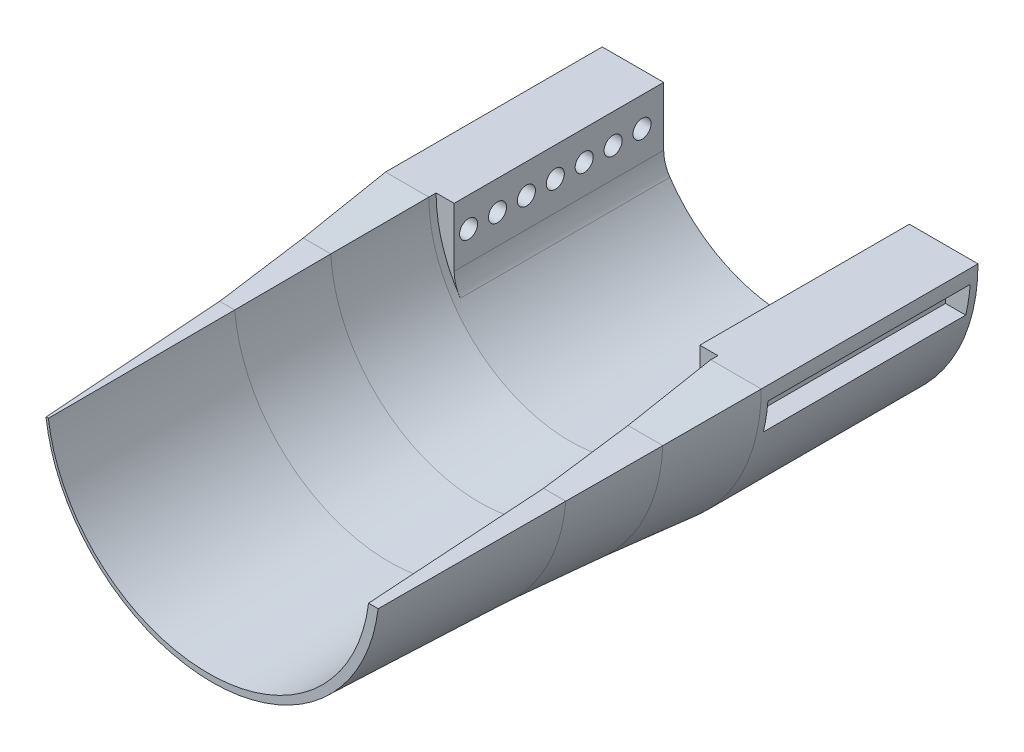
SolidWorks part; units mm, degrees
ref_plane "Front Plane" through (0, 0, 0) normal (0, 0, 1) x (1, 0, 0)
ref_plane "Top Plane" through (0, 0, 0) normal (0, 1, 0) x (1, 0, 0)
ref_plane "Right Plane" through (0, 0, 0) normal (1, 0, 0) x (0, 0, -1)
sketch "Sketch1" plane through (0, 0, 0) normal (0, 0, 1) x (1, 0, 0)
  line L0 (-39.8456, 0) -> (-40, 0) construction
  line L1 (-40, 10) -> (-40, -20) construction
  line L2 (-40, 0) -> (38, 0) construction
  line L3 (38, 20) -> (38, -20) construction
  line L4 (-39.8456, 0) -> (-52, 0)
  line L5 (38, 0) -> (52, 0)
  circle A0 centre (0, 0) radius 52 construction
  arc A1 (-40, 0) -> (38, 0) centre (-1, 0) ccw
  arc A2 (-52, 0) -> (52, 0) centre (0, 0) ccw
extrude "Boss-Extrude1" add sketch "Sketch1" along normal blind 60 contours L4 A2 L5 A1
sketch "Sketch2" plane through (0, 0, 60) normal (0, 0, 1) x (1, 0, 0)
  line L2 (-40, 0) -> (-52, 0)
  line L3 (52, 0) -> (38, 0)
  line L4 (-40, 0) -> (-52, 0)
  line L5 (52, 0) -> (38, 0)
  arc A2 (-52, 0) -> (52, 0) centre (0, 0) ccw
  arc A3 (-40, 0) -> (38, 0) centre (-1, 0) ccw
  arc A4 (-52, 0) -> (52, 0) centre (0, 0) ccw
  arc A5 (-40, 0) -> (38, 0) centre (-1, 0) ccw
  dimension "D1" = 0
extrude "Boss-Extrude2" add sketch "Sketch2" along normal blind 25 draft 5
sketch "Sketch3" plane through (0, 0, 85) normal (0, 0, 1) x (1, 0, 0)
  line L2 (-42.1291, -2.1872) -> (-49.7647, -2.1872)
  line L3 (49.7647, -2.1872) -> (40.1291, -2.1872)
  line L4 (-42.1291, -2.1872) -> (-49.7647, -2.1872)
  line L5 (49.7647, -2.1872) -> (40.1291, -2.1872)
  arc A2 (-42.1291, -2.1872) -> (40.1291, -2.1872) centre (-1, 0) ccw
  arc A3 (-49.7647, -2.1872) -> (49.7647, -2.1872) centre (0, 0) ccw
  arc A4 (-42.1291, -2.1872) -> (40.1291, -2.1872) centre (-1, 0) ccw
  arc A5 (-49.7647, -2.1872) -> (49.7647, -2.1872) centre (0, 0) ccw
  dimension "D1" = 0
extrude "Boss-Extrude3" add sketch "Sketch3" along normal blind 25 draft 4
sketch "Sketch4" plane through (0, 0, 110) normal (0, 0, 1) x (1, 0, 0)
  line L2 (-43.7547, -3.9354) -> (-47.9032, -3.9354)
  line L3 (47.9032, -3.9354) -> (41.7547, -3.9354)
  line L4 (-43.7547, -3.9354) -> (-47.9032, -3.9354)
  line L5 (47.9032, -3.9354) -> (41.7547, -3.9354)
  arc A2 (-43.7547, -3.9354) -> (41.7547, -3.9354) centre (-1, 0) ccw
  arc A3 (-47.9032, -3.9354) -> (47.9032, -3.9354) centre (0, 0) ccw
  arc A4 (-43.7547, -3.9354) -> (41.7547, -3.9354) centre (-1, 0) ccw
  arc A5 (-47.9032, -3.9354) -> (47.9032, -3.9354) centre (0, 0) ccw
  dimension "D1" = 0
extrude "Boss-Extrude4" add sketch "Sketch4" along normal blind 50 draft 2
sketch "Sketch5" plane through (0, 0, 0) normal (0, 0, -1) x (-1, 0, 0)
  line L0 (0, 0) -> (0, -63.5071) construction
  line L1 (-38, 0) -> (-33, 0)
  line L2 (-38, 0) -> (-38, -30)
  line L3 (-38, -30) -> (-33, -30)
  line L4 (-33, 0) -> (-33, -30)
  line L6 (40, 0) -> (35, 0)
  line L7 (40, 0) -> (40, -30)
  line L8 (40, -30) -> (35, -30)
  line L9 (35, 0) -> (35, -30)
  arc A0 (-38, 0) -> (40, 0) centre (1, 0) ccw construction
  dimension "D1" = 30
  dimension "D2" = 5
  dimension "D3" = 5
  dimension "D4" = 30
  dimension "D5" = 35
extrude "Boss-Extrude5" add sketch "Sketch5" against normal blind 58
fillet "Fillet1" radius 10 2 edges at (-35, -19.105, 29) (33, -19.105, 29)
sketch "Sketch6" plane through (33, 0, 0) normal (-1, 0, 0) x (0, 0, 1)
  line L0 (58, 0) -> (0, 0) construction
  line L2 (0, -16.2788) -> (0, 0) construction
  circle A0 centre (6, -8.14) radius 2.5
  circle A1 centre (14, -8.14) radius 2.5
  circle A2 centre (22, -8.14) radius 2.5
  circle A3 centre (30, -8.14) radius 2.5
  circle A4 centre (38, -8.14) radius 2.5
  circle A5 centre (46, -8.14) radius 2.5
  circle A6 centre (54, -8.14) radius 2.5
  dimension "D1" = 5
  dimension "D3" = 6
  dimension "D2" = 8.14
  dimension "D4" = 7
extrude "Cut-Extrude1" cut sketch "Sketch6" against normal through all both and the other way through all
sketch "Sketch7" plane through (-35, 0, 0) normal (1, 0, 0) x (0, 0, -1)
  line L0 (0, -52) -> (0, 0) construction
  line L1 (-58, -4) -> (-2, -4)
  line L2 (-58, -4) -> (-58, -12)
  line L3 (-58, -12) -> (-2, -12)
  line L4 (-2, -4) -> (-2, -12)
  line L5 (-60, 0) -> (0, 0) construction
  line L6 (-60, -52) -> (-60, 0) construction
  dimension "D1" = 2
  dimension "D2" = 4
  dimension "D3" = 12
  dimension "D4" = 2
extrude "Cut-Extrude2" cut sketch "Sketch7" against normal blind 58 from offset 10 offset against normal yes
mirror "Mirror1" about plane through (0, 0, 0) normal (1, 0, 0) of "Cut-Extrude2"
